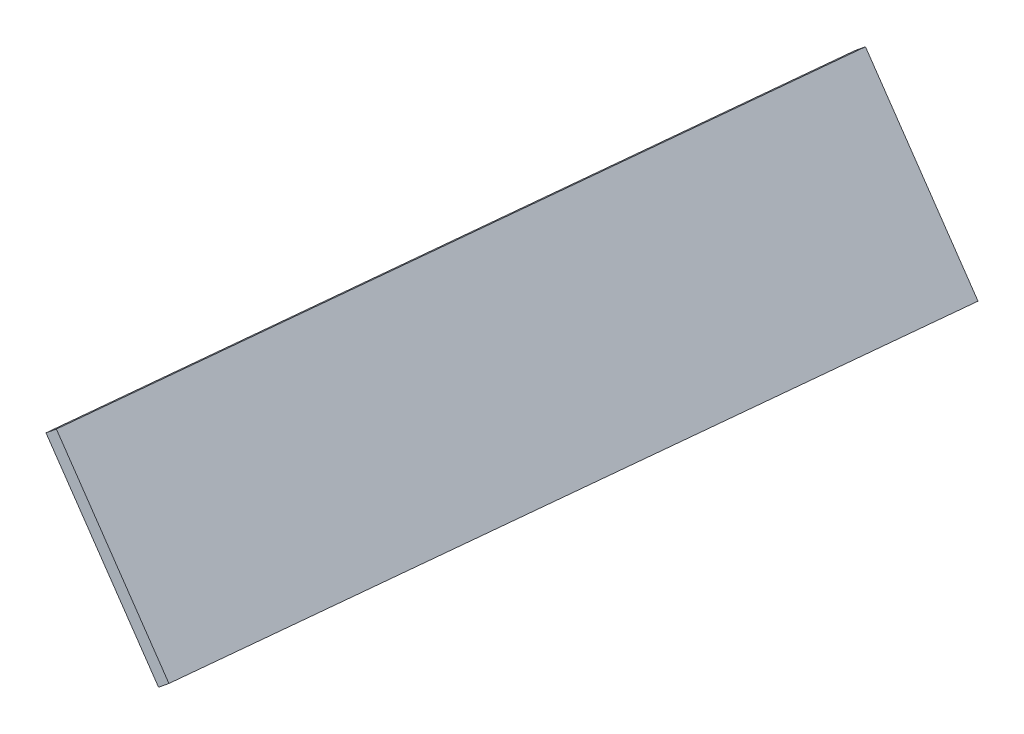
SolidWorks part; units mm, degrees
ref_plane "Front Plane" through (0, 0, 0) normal (0, 0, 1) x (1, 0, 0)
ref_plane "Top Plane" through (0, 0, 0) normal (0, 1, 0) x (1, 0, 0)
ref_plane "Right Plane" through (0, 0, 0) normal (1, 0, 0) x (0, 0, -1)
sketch "Sketch1" plane through (0, 0, 0) normal (0, 1, 0) x (1, 0, 0)
  line L1 (9.7493, 97.6641) -> (-79.705, 57.2752)
  line L2 (-79.705, 57.2752) -> (-89.4543, -40.389)
  line L3 (-89.4543, -40.389) -> (-9.7493, -97.6641)
  line L4 (-9.7493, -97.6641) -> (79.705, -57.2752)
  line L5 (79.705, -57.2752) -> (89.4543, 40.389)
  line L6 (89.4543, 40.389) -> (9.7493, 97.6641)
  circle A0 centre (0, 0) radius 85 construction
  point P1 (79.705, -57.2752)
  point P10 (0, 0)
  dimension "D1" = 170
ref_plane "Plane1" through (50.128, 41.7636, 5.004) normal (0.766, 0.6382, 0.0765) x (0.0993, 0, -0.9951)
sketch "Sketch2" plane through (50.128, 41.7636, 5.004) normal (0.766, 0.6382, 0.0765) x (0.0993, 0, -0.9951)
  line L0 (-49.0748, -54.2489) -> (49.0748, -54.2489) construction
  line L1 (-49.0748, -54.2489) -> (49.0748, -54.2489)
  line L2 (-49.0748, -54.2489) -> (-49.0748, -28.1114)
  line L3 (-49.0748, -28.1114) -> (49.0748, -28.1114)
  line L4 (49.0748, -54.2489) -> (49.0748, -28.1114)
  point P6 (0, -28.1114)
  point P8 (0, -54.2489)
  point P9 (20.6565, -54.6369)
  point P10 (0, 0)
  dimension "D2" = 90
extrude "Boss-Extrude1" add sketch "Sketch2" along normal blind 2
sketch "Bend-Lines1" [suppressed] plane through (0, 0, 0) normal (0, 1, 0) x (1, 0, 0)
sketch "Bounding-Box1" [suppressed] plane through (0, 0, 0) normal (0, 1, 0) x (1, 0, 0)
